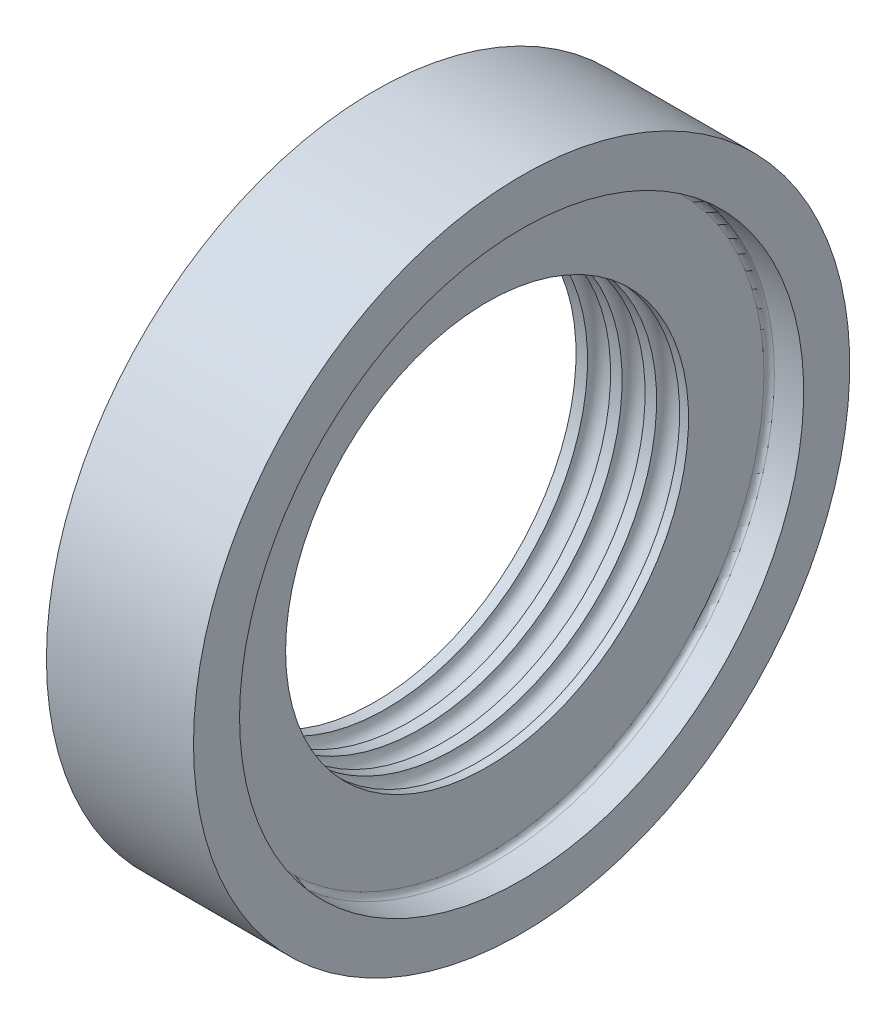
SolidWorks part; units mm, degrees
ref_plane "Front Plane" through (0, 0, 0) normal (0, 0, 1) x (1, 0, 0)
ref_plane "Top Plane" through (0, 0, 0) normal (0, 1, 0) x (1, 0, 0)
ref_plane "Right Plane" through (0, 0, 0) normal (1, 0, 0) x (0, 0, -1)
sketch "Sketch1" plane through (0, 0, 0) normal (0, 1, 0) x (1, 0, 0)
  line L0 (8.8, -19.25) -> (9.9, -19.25)
  line L1 (19.55, -19.25) -> (19.55, -26.95)
  line L2 (19.55, -26.95) -> (22.85, -26.95)
  line L3 (22.85, -26.95) -> (22.85, -31.35)
  line L4 (22.85, -31.35) -> (8.8, -31.35)
  line L5 (8.8, -31.35) -> (8.8, -19.25)
  line L6 (-55, 0) -> (55, 0) construction
  line L7 (4.1014, 0) -> (27.5345, 0) construction
  line L8 (12.1, -19.25) -> (13.2, -19.25)
  line L9 (15.4, -19.25) -> (16.5, -19.25)
  line L10 (18.7, -19.25) -> (19.55, -19.25)
  arc A0 (15.4, -19.25) -> (13.2, -19.25) centre (14.3, -19.25) cw
  arc A1 (12.1, -19.25) -> (9.9, -19.25) centre (11, -19.25) cw
  arc A2 (18.7, -19.25) -> (16.5, -19.25) centre (17.6, -19.25) cw
  dimension "D5" = 1.1
  dimension "D7" = 1.1
  dimension "D8" = 1.1
  dimension "D1" = 14.05
  dimension "D2" = 12.1
  dimension "D3" = 4.4
  dimension "D4" = 3.3
  dimension "D6" = 1.1
  dimension "D9" = 1.1
  dimension "D10" = 1.1
  dimension "D11" = 19.25
  dimension "D12" = 8.8
revolve "Revolve1" add sketch "Sketch1" angle 360 about L7
hole_wizard "Ø3.0mm Dowel Hole2" positions "Sketch7" profile "Sketch6" hole size "Ø3.0" standard "ANSI Metric"
sketch "Sketch7" plane through (8.8, 0, 0) normal (-1, 0, 0) x (0, 0, 1)
  line L0 (55, 0) -> (-55, 0) construction
  point P0 (-25.3, 0)
  point P4 (25.3, 0)
  dimension "D1" = 25.3
  dimension "D2" = 25.3
sketch "Sketch6" plane through (8.8, 0, -25.3) normal (0, 1, 0) x (0, 0, 1)
  line L0 (0, 0) -> (0, 6.0421)
  line L1 (0, 6.0421) -> (1.65, 4.95)
  line L2 (1.65, 4.95) -> (1.65, 0)
  line L5 (1.65, 0) -> (0, 0)
  line L10 (0, 6.0421) -> (-1.65, 4.95) construction
  line L11 (0, -6.35) -> (0, 107.95) construction
  dimension "Hole Dia." = 3.3
  dimension "Hole Depth" = 4.95
  dimension "Drill Angle" = 113
fillet "Fillet1" radius 0.5 1 edges at (19.55, 0, 26.95)
